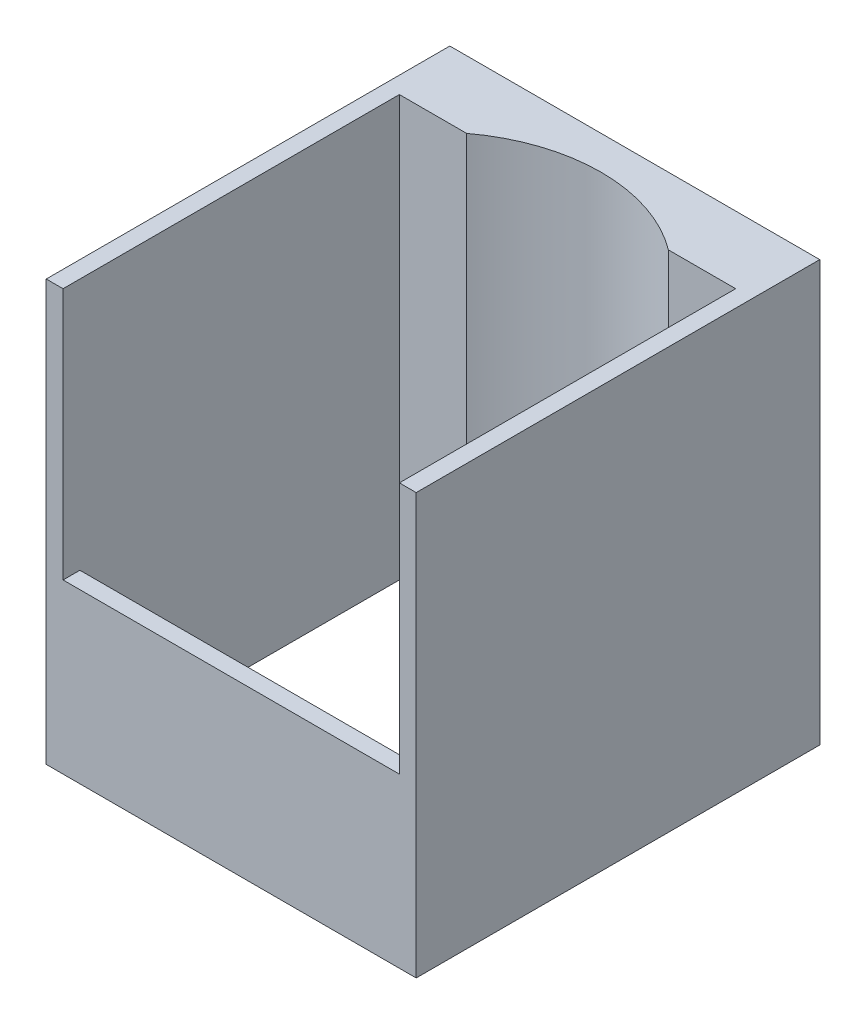
SolidWorks part; units mm, degrees
ref_plane "정면" through (0, 0, 0) normal (0, 0, 1) x (1, 0, 0)
ref_plane "윗면" through (0, 0, 0) normal (0, 1, 0) x (1, 0, 0)
ref_plane "우측면" through (0, 0, 0) normal (1, 0, 0) x (0, 0, -1)
sketch "Sketch1" plane through (0, 0, 0) normal (0, 1, 0) x (1, 0, 0)
  line L1 (0, 0) -> (670, 0)
  line L2 (0, 0) -> (0, 120)
  line L3 (0, 120) -> (670, 120)
  line L4 (670, 0) -> (670, 120)
  dimension "700" = 670
  dimension "D2" = 120
extrude "Boss-Extrude1" add sketch "Sketch1" along normal blind 530
sketch "Sketch2" plane through (0, 0, 0) normal (0, 0, 1) x (1, 0, 0)
  line L0 (0, 530) -> (0, 0) construction
  line L1 (10, 280) -> (110, 280)
  line L2 (10, 280) -> (10, 480)
  line L3 (10, 480) -> (110, 480)
  line L4 (110, 280) -> (110, 480)
  line L5 (0, 0) -> (670, 0) construction
  line L6 (120, 280) -> (120, 480)
  line L7 (120, 280) -> (220, 280)
  line L8 (220, 280) -> (220, 480)
  line L9 (120, 480) -> (220, 480)
  line L10 (230, 280) -> (230, 480)
  line L11 (230, 280) -> (330, 280)
  line L12 (330, 280) -> (330, 480)
  line L13 (230, 480) -> (330, 480)
  line L14 (340, 280) -> (340, 480)
  line L15 (340, 280) -> (440, 280)
  line L16 (440, 280) -> (440, 480)
  line L17 (340, 480) -> (440, 480)
  line L18 (450, 280) -> (450, 480)
  line L19 (450, 280) -> (550, 280)
  line L20 (550, 280) -> (550, 480)
  line L21 (450, 480) -> (550, 480)
  line L22 (560, 280) -> (560, 480)
  line L23 (560, 280) -> (660, 280)
  line L24 (660, 280) -> (660, 480)
  line L25 (560, 480) -> (660, 480)
  line L27 (10, 10) -> (660, 10)
  line L28 (10, 10) -> (10, 260)
  line L29 (10, 260) -> (660, 260)
  line L30 (660, 10) -> (660, 260)
  line L31 (0, 530) -> (670, 530) construction
  point P6 (10, 380)
  dimension "D1" = 100
  dimension "D2" = 200
  dimension "D3" = 10
  dimension "D4" = 50
  dimension "D6" = 10
  dimension "D7" = 20
  dimension "D5" = 6
extrude "Cut-Extrude1" cut sketch "Sketch2" against normal blind 100
sketch "Sketch3" plane through (0, 530, 0) normal (0, 1, 0) x (1, 0, 0)
  line L1 (670, 120) -> (0, 120) construction
  line L2 (0, 120) -> (0, 0) construction
  circle A0 centre (60, 60) radius 50
  circle A1 centre (170, 60) radius 50
  circle A2 centre (280, 60) radius 50
  circle A3 centre (390, 60) radius 50
  circle A4 centre (500, 60) radius 50
  circle A5 centre (610, 60) radius 50
  dimension "D1" = 100
  dimension "D2" = 10
  dimension "D3" = 10
  dimension "D4" = 6
extrude "Cut-Extrude2" cut sketch "Sketch3" against normal blind 260
hole_wizard "Ø12.0 (12) Diameter Hole2" positions "3DSketch1" profile "Sketch7" hole size "Ø12.0" standard "Ansi Metric"
sketch3d "3DSketch1"
  point P0 (59.7046, 270, -102.4117)
  point P2 (171.5567, 270, -102.6076)
  point P4 (280.8723, 270, -102.3969)
  point P6 (391.0687, 270, -102.7535)
  point P8 (500.7133, 270, -101.754)
  point P10 (609.5165, 270, -101.1227)
sketch "Sketch7" plane through (59.7046, 270, -102.4117) normal (1, 0, 0) x (0, 0, 1)
  line L0 (0, 0) -> (0, 33.6052)
  line L1 (0, 33.6052) -> (6, 30)
  line L2 (6, 30) -> (6, 0)
  line L5 (6, 0) -> (0, 0)
  line L10 (0, 33.6052) -> (-6, 30) construction
  line L11 (0, -6.35) -> (0, 107.95) construction
  dimension "구멍 지름" = 12
  dimension "구멍 깊이" = 30
  dimension "드릴 각도" = 118
sketch "Sketch8" plane through (0, 0, 0) normal (0, 0, 1) x (1, 0, 0)
  line L0 (660, 280) -> (660, 480) construction
  line L1 (10, 280) -> (660, 280)
  line L2 (10, 280) -> (10, 330)
  line L3 (10, 330) -> (660, 330)
  line L4 (660, 280) -> (660, 330)
  dimension "D1" = 50
extrude "Boss-Extrude2" add sketch "Sketch8" against normal blind 5
sketch "Sketch9" plane through (670, 0, 0) normal (1, 0, 0) x (0, 0, -1)
  line L0 (0, 530) -> (0, 0) construction
  line L1 (10, 10) -> (20, 10)
  line L2 (10, 10) -> (10, 260)
  line L3 (10, 260) -> (20, 260)
  line L4 (20, 10) -> (20, 260)
  line L5 (0, 0) -> (120, 0) construction
  dimension "D1" = 10
  dimension "D2" = 10
  dimension "D3" = 10
  dimension "D4" = 250
extrude "Cut-Extrude3" cut sketch "Sketch9" against normal blind 717
sketch "Sketch10" plane through (0, 10, 0) normal (0, 1, 0) x (1, 0, 0)
  line L0 (670, 120) -> (0, 120) construction
  line L1 (365, 61.9436) -> (350, 87.9243)
  line L2 (350, 87.9243) -> (320, 87.9243)
  line L3 (320, 87.9243) -> (305, 61.9436)
  line L4 (305, 61.9436) -> (320, 35.9628)
  line L5 (320, 35.9628) -> (350, 35.9628)
  line L6 (350, 35.9628) -> (365, 61.9436)
  line L7 (0, 120) -> (0, 0) construction
  circle A0 centre (335, 61.9436) radius 25.9808 construction
  dimension "D1" = 60
  dimension "D2" = 305
extrude "Cut-Extrude4" cut sketch "Sketch10" against normal blind 5
sketch "Sketch11" plane through (0, 0, -100) normal (0, 0, 1) x (1, 0, 0)
  line L0 (10, 10) -> (660, 10) construction
  line L1 (250, 10) -> (260, 10)
  line L2 (250, 10) -> (250, 110)
  line L3 (250, 110) -> (260, 110)
  line L4 (260, 10) -> (260, 110)
  line L5 (660, 10) -> (660, 260) construction
  line L6 (410, 10) -> (420, 10)
  line L7 (410, 10) -> (410, 110)
  line L8 (410, 110) -> (420, 110)
  line L9 (420, 10) -> (420, 110)
  line L10 (25, 198.4569) -> (325, 145.5588)
  line L11 (325, 145.5588) -> (325, 122.0178)
  line L12 (325, 122.0178) -> (345, 122.0178)
  line L13 (345, 122.0178) -> (345, 145.5588)
  line L14 (345, 145.5588) -> (645, 198.4569)
  line L15 (645, 198.4569) -> (25, 198.4569)
  point P18 (345, 133.7883)
  dimension "D1" = 10
  dimension "D2" = 10
  dimension "D3" = 100
  dimension "D4" = 100
  dimension "D5" = 150
  dimension "D6" = 240
  dimension "D7" = 20
  dimension "D8" = 65
  dimension "D9" = 100
  dimension "D10" = 620
  dimension "D11" = 100
extrude "Boss-Extrude3" add sketch "Sketch11" along normal blind 78 separate body
sketch "Sketch12" plane through (0, 0, -100) normal (0, 0, 1) x (1, 0, 0)
  line L0 (660, 260) -> (10, 260) construction
  line L1 (75.1986, 260) -> (95.1986, 260)
  line L2 (75.1986, 260) -> (75.1986, 230)
  line L3 (75.1986, 230) -> (95.1986, 230)
  line L4 (95.1986, 260) -> (95.1986, 230)
  line L5 (65.1986, 260) -> (65.1986, 240) construction
  line L6 (185.1986, 260) -> (185.1986, 230)
  line L7 (185.1986, 260) -> (205.1986, 260)
  line L8 (205.1986, 260) -> (205.1986, 230)
  line L9 (185.1986, 230) -> (205.1986, 230)
  line L10 (295.1986, 260) -> (295.1986, 230)
  line L11 (295.1986, 260) -> (315.1986, 260)
  line L12 (315.1986, 260) -> (315.1986, 230)
  line L13 (295.1986, 230) -> (315.1986, 230)
  line L14 (405.1986, 260) -> (405.1986, 230)
  line L15 (405.1986, 260) -> (425.1986, 260)
  line L16 (425.1986, 260) -> (425.1986, 230)
  line L17 (405.1986, 230) -> (425.1986, 230)
  line L18 (515.1986, 260) -> (515.1986, 230)
  line L19 (515.1986, 260) -> (535.1986, 260)
  line L20 (535.1986, 260) -> (535.1986, 230)
  line L21 (515.1986, 230) -> (535.1986, 230)
  line L22 (625.1986, 260) -> (625.1986, 230)
  line L23 (625.1986, 260) -> (645.1986, 260)
  line L24 (645.1986, 260) -> (645.1986, 230)
  line L25 (625.1986, 230) -> (645.1986, 230)
  dimension "D1" = 20
  dimension "D2" = 30
  dimension "D3" = 10
  dimension "D4" = 6
extrude "Cut-Extrude5" cut sketch "Sketch12" against normal blind 80
sketch "Sketch15" plane through (345, 0, 0) normal (1, 0, 0) x (0, 0, -1)
  line L0 (20, 10) -> (20, 260) construction
  line L1 (20, 121.4638) -> (50, 121.4638)
  line L2 (20, 121.4638) -> (20, 145)
  line L3 (20, 145) -> (50, 145)
  line L4 (50, 121.4638) -> (50, 145)
  line L5 (120, 530) -> (120, 0) construction
  line L6 (100, 116.0134) -> (70, 116.0134)
  line L7 (100, 116.0134) -> (100, 145)
  line L8 (100, 145) -> (70, 145)
  line L9 (70, 116.0134) -> (70, 145)
  line L10 (20, 260) -> (10, 260) construction
  dimension "D1" = 20
  dimension "D2" = 20
  dimension "D3" = 115
  dimension "D4" = 30
extrude "Cut-Extrude7" cut sketch "Sketch15" against normal blind 35
shell "Shell1" thickness 3
sketch "Sketch16" plane through (0, 122.0178, 0) normal (0, -1, 0) x (1, 0, 0)
  line L0 (345, -50) -> (325, -50) construction
  line L1 (328, -53) -> (342, -53)
  line L2 (328, -53) -> (328, -67)
  line L3 (328, -67) -> (342, -67)
  line L4 (342, -53) -> (342, -67)
  line L5 (325, -50) -> (325, -70) construction
  line L6 (345, -50) -> (345, -70) construction
  line L7 (325, -70) -> (345, -70) construction
  dimension "D1" = 3
  dimension "D2" = 3
  dimension "D3" = 3
  dimension "D4" = 3
extrude "Cut-Extrude8" cut sketch "Sketch16" against normal blind 35
sketch "Sketch17" plane through (0, 0, 0) normal (0, 0, 1) x (1, 0, 0)
  text T0 "<b>DIFF_USER</b>" font "Britannic Bold" height in points 72
extrude "Boss-Extrude4" add sketch "Sketch17" along normal blind 5
sketch "Sketch18" plane through (0, 0, 0) normal (0, 0, 1) x (1, 0, 0)
  line L0 (670, 530) -> (670, 0) construction
  line L1 (0, 0) -> (670, 0)
  line L2 (0, 0) -> (0, 280)
  line L3 (0, 280) -> (670, 280)
  line L4 (670, 0) -> (670, 280)
  dimension "D1" = 280
extrude "Cut-Extrude10" cut sketch "Sketch18" against normal blind 159
sketch "Sketch19" plane through (0, 0, 0) normal (0, 0, 1) x (1, 0, 0)
  line L0 (0, 530) -> (670, 530) construction
  line L1 (0, 280) -> (115, 280)
  line L2 (0, 280) -> (0, 530)
  line L3 (0, 530) -> (115, 530)
  line L4 (115, 280) -> (115, 530)
  line L6 (670, 280) -> (225, 280)
  line L7 (670, 280) -> (670, 530)
  line L8 (670, 530) -> (225, 530)
  line L9 (225, 280) -> (225, 530)
  dimension "D1" = 115
  dimension "D2" = 445
extrude "Cut-Extrude11" cut sketch "Sketch19" against normal through all both and the other way through all
sketch "Sketch20" plane through (0, 0, 0) normal (0, 0, 1) x (1, 0, 0)
  line L0 (225, 280) -> (225, 530) construction
  line L1 (115, 530) -> (225, 530)
  line L2 (115, 530) -> (115, 405)
  line L3 (115, 405) -> (225, 405)
  line L4 (225, 530) -> (225, 405)
  dimension "D1" = 125
extrude "Cut-Extrude12" cut sketch "Sketch20" against normal through all both and the other way through all
